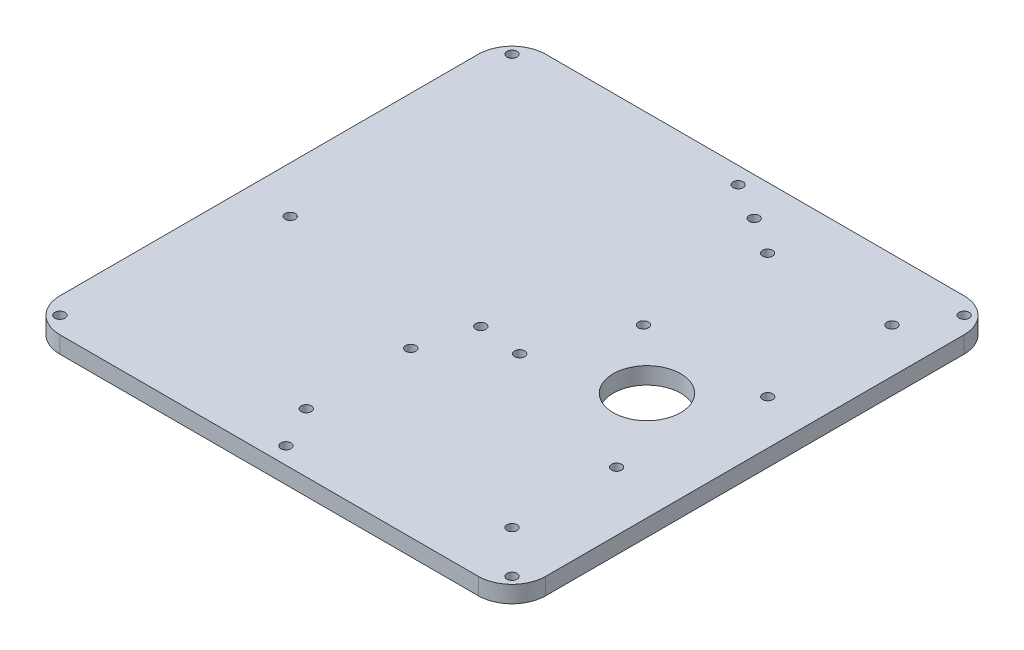
SolidWorks part; units mm, degrees
ref_plane "Front Plane" through (0, 0, 0) normal (0, 0, 1) x (1, 0, 0)
ref_plane "Top Plane" through (0, 0, 0) normal (0, 1, 0) x (1, 0, 0)
ref_plane "Right Plane" through (0, 0, 0) normal (1, 0, 0) x (0, 0, -1)
sketch "Sketch1" plane through (0, 0, 0) normal (0, 1, 0) x (1, 0, 0)
  line L1 (-72, 72) -> (72, 72)
  line L2 (-72, 72) -> (-72, -72)
  line L3 (-72, -72) -> (72, -72)
  line L4 (72, 72) -> (72, -72)
  point P0 (0, 0)
  dimension "D1" = 144
  dimension "D2" = 72
  dimension "D3" = 72
extrude "Boss-Extrude1" add sketch "Sketch1" along normal blind 5
sketch "Sketch2" plane through (0, 5, 0) normal (0, 1, 0) x (1, 0, 0)
  line L0 (72, 72) -> (-72, 72) construction
  line L2 (0, 72) -> (0, -72) construction
  line L3 (-72, -72) -> (72, -72) construction
  line L4 (72, 0) -> (-72, 0) construction
  line L5 (72, -72) -> (72, 72) construction
  line L6 (-72, 72) -> (-72, -72) construction
  circle A0 centre (-67, 67) radius 1.5
  circle A1 centre (-67, -67) radius 1.5
  circle A2 centre (67, 67) radius 1.5
  circle A3 centre (67, -67) radius 1.5
  dimension "D1" = 5
  dimension "D3" = 3
  dimension "D2" = 5
extrude "Cut-Extrude1" cut sketch "Sketch2" against normal up to surface (5 mm away) up to face at (0, 0, 0)
fillet "Fillet1" radius 10 4 edges at (-72, 2.5, -72) (72, 2.5, -72) (-72, 2.5, 72) (72, 2.5, 72)
sketch "Sketch3" plane through (0, 0, 0) normal (0, -1, 0) x (1, 0, 0)
  circle A0 centre (11.02, 8.75) radius 1.5
  circle A1 centre (11.02, -60.75) radius 1.5
  dimension "D1" = 3
  dimension "D2" = 3
extrude "Cut-Extrude2" cut sketch "Sketch3" against normal up to surface (5 mm away) up to face at (-67, 5, 65.5)
sketch "Sketch4" plane through (0, 5, 0) normal (0, 1, 0) x (1, 0, 0)
  circle A0 centre (21.95, 53.8037) radius 1.5
  circle A1 centre (58.8, 53.8037) radius 1.5
  circle A2 centre (21.95, 16.9963) radius 1.5
  circle A3 centre (58.8, 16.9963) radius 1.5
  circle A4 centre (-6.5, -23.5) radius 1.5
  circle A5 centre (54.5, -23.5) radius 1.5
  circle A6 centre (-6.5, -54.5) radius 1.5
  circle A7 centre (54.5, -54.5) radius 1.5
  dimension "D1" = 3
extrude "Cut-Extrude3" cut sketch "Sketch4" against normal up to surface (5 mm away) up to face at (11.02, 0, 7.25)
sketch "Sketch6" plane through (0, 0, 0) normal (0, -1, 0) x (1, 0, 0)
  circle A0 centre (40, 0) radius 10
  dimension "D1" = 20
  dimension "D2" = 40
extrude "Cut-Extrude4" cut sketch "Sketch6" against normal up to surface (5 mm away) up to face at (-6.5, 5, 25)
sketch "Sketch7" plane through (0, 5, 0) normal (0, 1, 0) x (1, 0, 0)
  circle A0 centre (-58.25, -7.5) radius 1.5
  circle A1 centre (-1.75, -7.5) radius 1.5
  dimension "D1" = 3
  dimension "D2" = 3
extrude "Cut-Extrude5" cut sketch "Sketch7" against normal up to surface (5 mm away) up to face at (40, 0, -10)
sketch "Sketch8" plane through (0, 5, 0) normal (0, 1, 0) x (1, 0, 0)
  circle A0 centre (0, 67) radius 1.5
  circle A1 centre (0, -67) radius 1.5
  dimension "D1" = 3
  dimension "D2" = 3
extrude "Cut-Extrude6" cut sketch "Sketch8" against normal up to surface (5 mm away) up to face at (-58.25, 0, 9)
